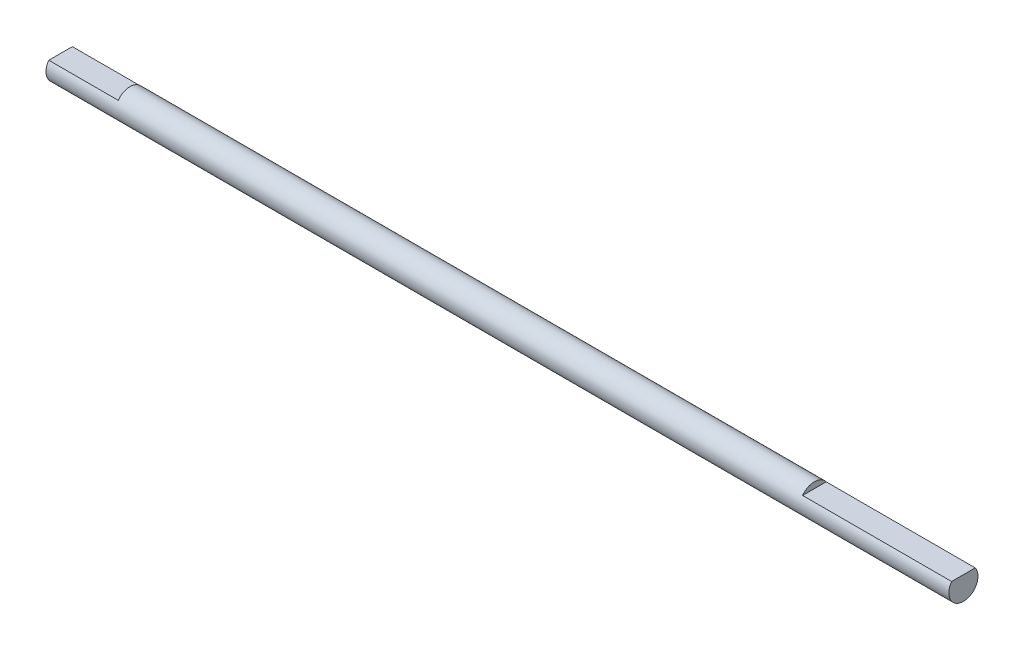
SolidWorks part; units mm, degrees
ref_plane "Front Plane" through (0, 0, 0) normal (0, 0, 1) x (1, 0, 0)
ref_plane "Top Plane" through (0, 0, 0) normal (0, 1, 0) x (1, 0, 0)
ref_plane "Right Plane" through (0, 0, 0) normal (1, 0, 0) x (0, 0, -1)
sketch "Sketch1" plane through (0, 0, 0) normal (1, 0, 0) x (0, 0, -1)
  circle A0 centre (0, 0) radius 4
  dimension "D1" = 8
extrude "Boss-Extrude1" add sketch "Sketch1" along normal mid plane 247.65
sketch "Sketch3" plane through (0, 0, 0) normal (0, 0, 1) x (1, 0, 0)
  line L0 (123.825, 4) -> (-123.825, 4) construction
  line L1 (-123.825, 2.35) -> (-104.775, 2.35)
  line L2 (-123.825, 2.35) -> (-123.825, 4)
  line L3 (-123.825, 4) -> (-104.775, 4)
  line L4 (-104.775, 2.35) -> (-104.775, 4)
  line L5 (-123.825, 2.35) -> (-104.775, 4) construction
  line L6 (-123.825, 4) -> (-104.775, 2.35) construction
  line L7 (-123.825, 4) -> (-123.825, -4) construction
  line L8 (123.825, -4) -> (123.825, 4) construction
  line L9 (82.9469, 4) -> (123.825, 4)
  line L10 (82.9469, 4) -> (82.9469, 2.35)
  line L11 (82.9469, 2.35) -> (123.825, 2.35)
  line L12 (123.825, 4) -> (123.825, 2.35)
  line L13 (82.9469, 4) -> (123.825, 2.35) construction
  line L14 (82.9469, 2.35) -> (123.825, 4) construction
  point P0 (-114.3, 3.175)
  point P10 (103.3859, 3.175)
  dimension "D1" = 1.65
  dimension "D2" = 19.05
  dimension "D3" = 40.8781
extrude "Cut-Extrude1" cut sketch "Sketch3" against normal through all both and the other way through all
